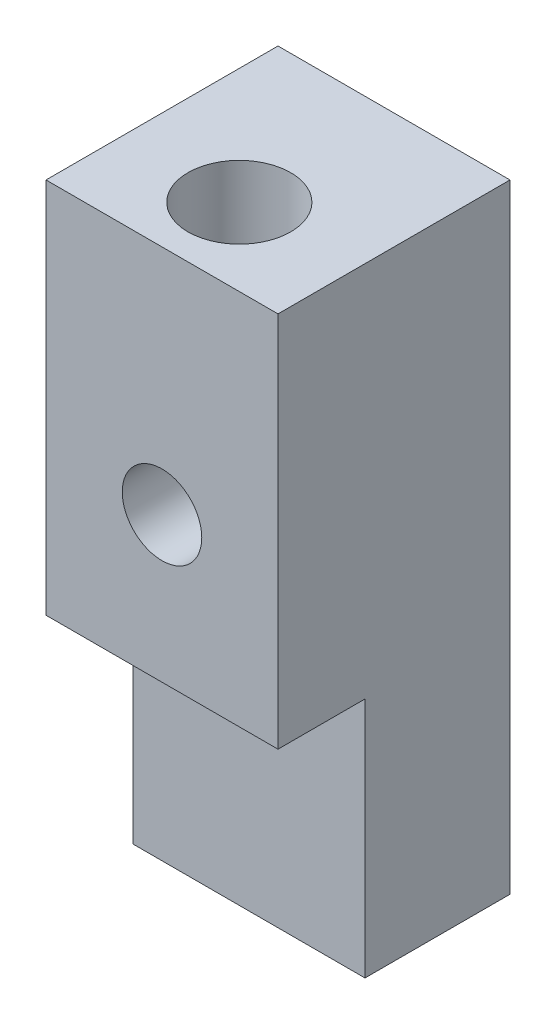
SolidWorks part; units mm, degrees
ref_plane "Front" through (0, 0, 0) normal (0, 0, 1) x (1, 0, 0)
ref_plane "Top" through (0, 0, 0) normal (0, 1, 0) x (1, 0, 0)
ref_plane "Right" through (0, 0, 0) normal (1, 0, 0) x (0, 0, -1)
sketch "Sketch1" plane through (0, 0, 0) normal (1, 0, 0) x (0, 0, -1)
  line L0 (0, 0) -> (11.9062, 0)
  line L1 (11.9062, 0) -> (11.9062, 50.8)
  line L2 (11.9062, 50.8) -> (-7.1438, 50.8)
  line L3 (-7.1438, 50.8) -> (-7.1438, 19.8438)
  line L4 (-7.1438, 19.8438) -> (0, 19.8438)
  line L5 (0, 19.8438) -> (0, 0)
  dimension "D1" = 19.05
  dimension "D2" = 50.8
  dimension "D3" = 7.1437
  dimension "D4" = 19.8438
extrude "Extrude1" add sketch "Sketch1" along normal blind 19.05
hole_wizard "5/16-18 Tapped Hole1" positions "Sketch3" profile "Sketch2" tap size "5/16-18" standard "Ansi Inch" end condition through all
sketch "Sketch3" plane through (0, 0, 7.1437) normal (0, 0, 1) x (1, 0, 0)
  line L0 (0, 50.8) -> (0, 19.8438) construction
  line L1 (19.05, 50.8) -> (0, 50.8) construction
  point P0 (9.525, 31.75)
  dimension "D1" = 9.525
  dimension "D2" = 19.05
cosmetic thread "Hole Thread1" parameters "D2"=7.9375
sketch "Sketch2" plane through (9.525, 31.75, 7.1437) normal (1, 0, 0) x (0, -1, 0)
  line L0 (0, 0) -> (0, 19.05)
  line L1 (0, 19.05) -> (3.2639, 19.05)
  line L2 (3.2639, 19.05) -> (3.2639, 0)
  line L5 (3.2639, 0) -> (0, 0)
  line L11 (0, -6.35) -> (0, 107.95) construction
  dimension "Thru Tap Drill Dia." = 6.5278
  dimension "Thru Tap Drill Depth" = 19.05
hole_wizard "3/8-24 Tapped Hole1" positions "Sketch5" profile "Sketch4" tap size "3/8-24" standard "Ansi Inch"
sketch "Sketch5" plane through (0, 50.8, 0) normal (0, 1, 0) x (-1, 0, 0)
  line L0 (0, -11.9062) -> (0, 7.1438) construction
  line L1 (-19.05, 7.1438) -> (0, 7.1438) construction
  point P0 (-9.525, 0.7938)
  dimension "D1" = 9.525
  dimension "D2" = 6.35
sketch "Sketch4" plane through (9.525, 50.8, 0.7938) normal (1, 0, 0) x (0, 0, 1)
  line L0 (0, 0) -> (0, 15.2335)
  line L1 (0, 15.2335) -> (4.2164, 12.7)
  line L2 (4.2164, 12.7) -> (4.2164, 0)
  line L5 (4.2164, 0) -> (0, 0)
  line L10 (0, 15.2335) -> (-4.2164, 12.7) construction
  line L11 (0, -6.35) -> (0, 107.95) construction
  dimension "Tap Drill Dia." = 8.4328
  dimension "Tap Drill Depth" = 12.7
  dimension "Drill Angle" = 118
cosmetic thread "Hole Thread2" parameters "D1"=19.05, "D2"=9.525
